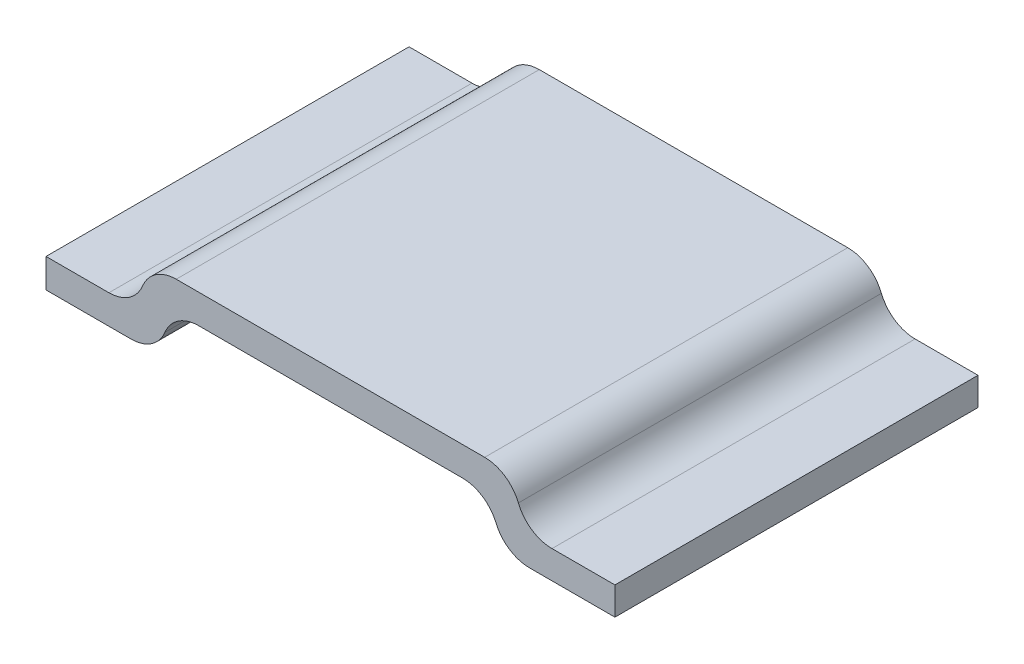
SolidWorks part; units mm, degrees
material "1060 Alloy"
ref_plane "Front Plane" through (0, 0, 0) normal (0, 0, 1) x (1, 0, 0)
ref_plane "Top Plane" through (0, 0, 0) normal (0, 1, 0) x (1, 0, 0)
ref_plane "Right Plane" through (0, 0, 0) normal (1, 0, 0) x (0, 0, -1)
sketch "Sketch1" plane through (0, 0, 0) normal (0, 0, 1) x (1, 0, 0)
  line L0 (-12.7, 0) -> (12.7, 0)
  line L1 (12.7, 0) -> (13.5507, -3.175)
  line L2 (13.5507, -3.175) -> (19.9007, -3.175)
  line L3 (0, -1.7463) -> (0, 1.7463) construction
  line L4 (-13.5507, -3.175) -> (-19.9007, -3.175)
  line L5 (-12.7, 0) -> (-13.5507, -3.175)
  line L6 (-11.1408, -2.032) -> (11.1408, -2.032)
  line L7 (11.1408, -2.032) -> (11.9713, -5.1316)
  line L8 (11.9713, -5.1316) -> (19.9007, -5.1316)
  line L9 (-11.1408, -2.032) -> (-11.9915, -5.207)
  line L10 (-11.9915, -5.207) -> (-19.9007, -5.207)
  line L11 (-19.9007, -5.207) -> (-19.9007, -3.175)
  line L12 (19.9007, -5.1316) -> (19.9007, -3.175)
  point P3 (11.5561, -3.5818)
  point P4 (0, 0)
  point P13 (0, 0)
  dimension "D1" = 12.7
  dimension "D2" = 6.35
  dimension "D3" = 3.175
  dimension "D4" = 75
  dimension "D5" = 2.032
  dimension "D6" = 2.032
  dimension "D7" = 2.032
  dimension "D8" = 1.9566
  dimension "D9" = 2.032
extrude "Boss-Extrude1" add sketch "Sketch1" along normal blind 25.4
fillet "Fillet1" radius 2.54 1 edges at (13.5507, -3.175, 12.7)
fillet "Fillet2" radius 2.54 1 edges at (12.7, 0, 12.7)
fillet "Fillet3" radius 2.54 2 edges at (-11.9915, -5.207, 12.7) (11.9713, -5.1316, 12.7)
fillet "Fillet5" radius 2.54 3 edges at (-13.5507, -3.175, 12.7) (11.1408, -2.032, 12.7) (-11.1408, -2.032, 12.7)
fillet "Fillet6" radius 2.54 1 edges at (-12.7, 0, 12.7)
